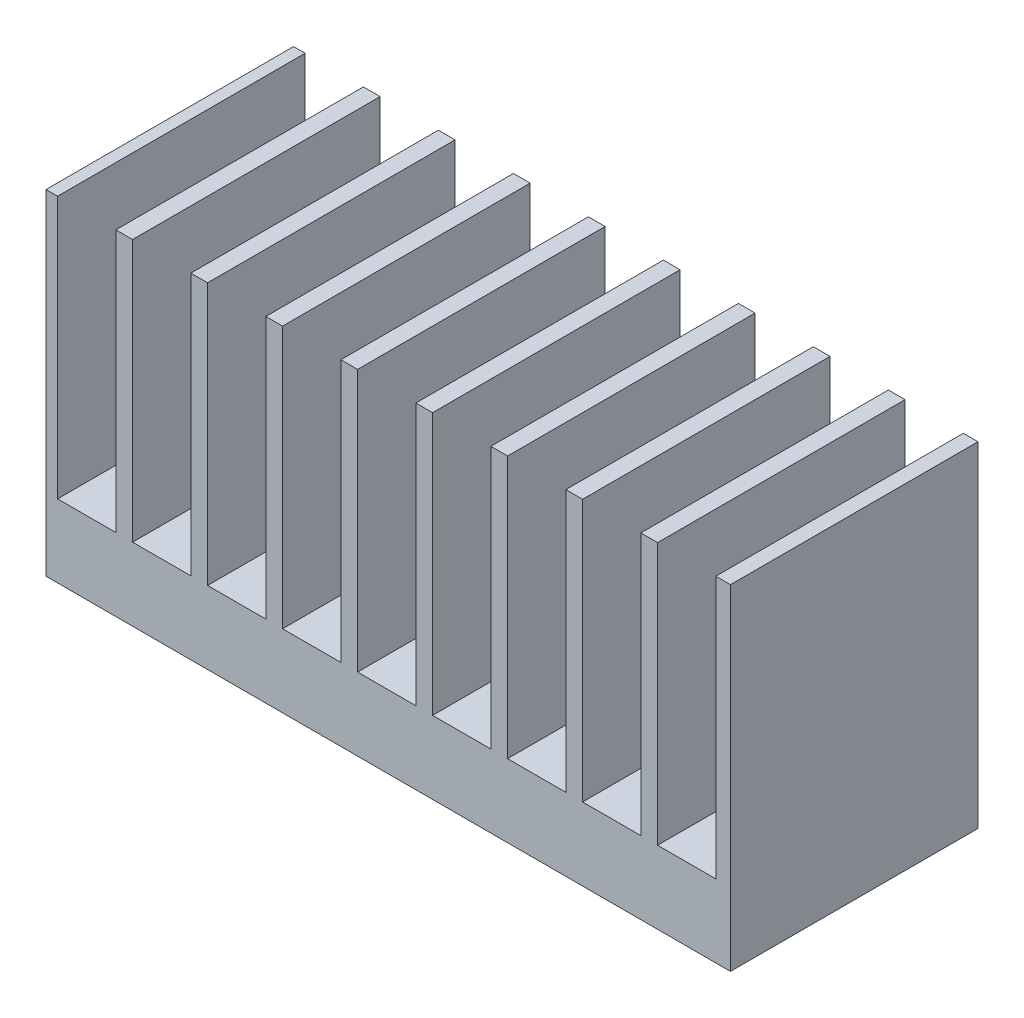
SolidWorks part; units mm, degrees
ref_plane "Front Plane" through (0, 0, 0) normal (0, 0, 1) x (1, 0, 0)
ref_plane "Top Plane" through (0, 0, 0) normal (0, 1, 0) x (1, 0, 0)
ref_plane "Right Plane" through (0, 0, 0) normal (1, 0, 0) x (0, 0, -1)
sketch "Sketch1" plane through (0, 0, 0) normal (0, 1, 0) x (1, 0, 0)
  line L1 (-23.5, 8.5) -> (23.5, 8.5)
  line L2 (-23.5, 8.5) -> (-23.5, -8.5)
  line L3 (-23.5, -8.5) -> (23.5, -8.5)
  line L4 (23.5, 8.5) -> (23.5, -8.5)
  line L5 (-23.5, 8.5) -> (23.5, -8.5) construction
  line L6 (-23.5, -8.5) -> (23.5, 8.5) construction
  point P0 (0, 0)
extrude "Boss-Extrude1" add sketch "Sketch1" along normal blind 23
sketch "Sketch2" plane through (0, 0, 8.5) normal (0, 0, 1) x (1, 0, 0)
  line L0 (-23.5, 23) -> (23.5, 23) construction
  line L1 (-22.7048, 23) -> (-18.7048, 23)
  line L2 (-22.7048, 23) -> (-22.7048, 5)
  line L3 (-22.7048, 5) -> (-18.7048, 5)
  line L4 (-18.7048, 23) -> (-18.7048, 5)
  line L5 (-23.5, 0) -> (23.5, 0) construction
  line L6 (-17.5548, 23) -> (-13.5548, 23)
  line L7 (-17.5548, 23) -> (-17.5548, 5)
  line L8 (-17.5548, 5) -> (-13.5548, 5)
  line L9 (-13.5548, 23) -> (-13.5548, 5)
  line L10 (-12.4048, 23) -> (-8.4048, 23)
  line L11 (-12.4048, 23) -> (-12.4048, 5)
  line L12 (-12.4048, 5) -> (-8.4048, 5)
  line L13 (-8.4048, 23) -> (-8.4048, 5)
  line L14 (-7.2548, 23) -> (-3.2548, 23)
  line L15 (-7.2548, 23) -> (-7.2548, 5)
  line L16 (-7.2548, 5) -> (-3.2548, 5)
  line L17 (-3.2548, 23) -> (-3.2548, 5)
  line L18 (-2.1048, 23) -> (1.8952, 23)
  line L19 (-2.1048, 23) -> (-2.1048, 5)
  line L20 (-2.1048, 5) -> (1.8952, 5)
  line L21 (1.8952, 23) -> (1.8952, 5)
  line L22 (3.0452, 23) -> (7.0452, 23)
  line L23 (3.0452, 23) -> (3.0452, 5)
  line L24 (3.0452, 5) -> (7.0452, 5)
  line L25 (7.0452, 23) -> (7.0452, 5)
  line L26 (8.1952, 23) -> (12.1952, 23)
  line L27 (8.1952, 23) -> (8.1952, 5)
  line L28 (8.1952, 5) -> (12.1952, 5)
  line L29 (12.1952, 23) -> (12.1952, 5)
  line L30 (13.3452, 23) -> (17.3452, 23)
  line L31 (13.3452, 23) -> (13.3452, 5)
  line L32 (13.3452, 5) -> (17.3452, 5)
  line L33 (17.3452, 23) -> (17.3452, 5)
  line L34 (18.4952, 23) -> (22.4952, 23)
  line L35 (18.4952, 23) -> (18.4952, 5)
  line L36 (18.4952, 5) -> (22.4952, 5)
  line L37 (22.4952, 23) -> (22.4952, 5)
  dimension "D1" = 5
  dimension "D2" = 9
extrude "Cut-Extrude1" cut sketch "Sketch2" against normal through all
sketch "Sketch3" plane through (0, 0, 0) normal (0, -1, 0) x (1, 0, 0)
  line L0 (0, 0) -> (0, 15.1936) construction
  circle A0 centre (-20.6007, 0) radius 2
  circle A1 centre (20.6007, 0) radius 2
extrude "Cut-Extrude2" cut sketch "Sketch3" against normal blind 8
